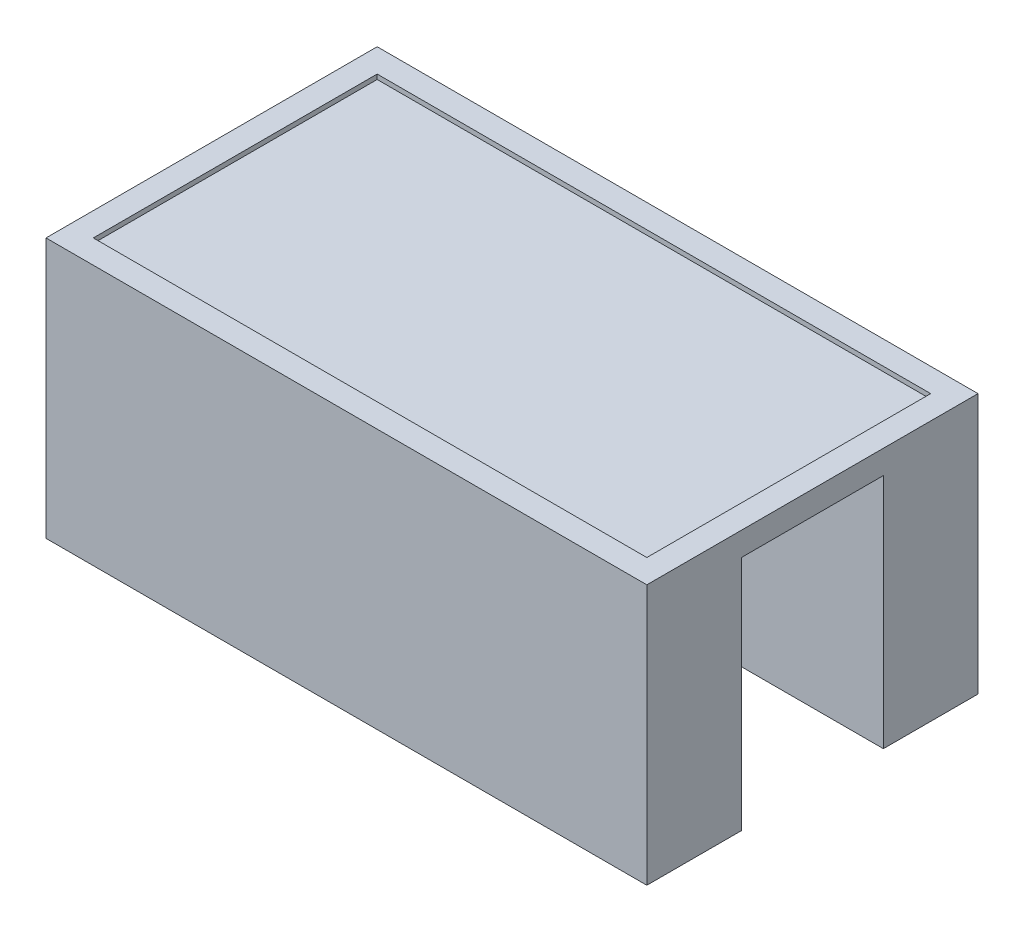
SolidWorks part; units mm, degrees
ref_plane "Front Plane" through (0, 0, 0) normal (0, 0, 1) x (1, 0, 0)
ref_plane "Top Plane" through (0, 0, 0) normal (0, 1, 0) x (1, 0, 0)
ref_plane "Right Plane" through (0, 0, 0) normal (1, 0, 0) x (0, 0, -1)
sketch "Sketch2" plane through (0, 0, 0) normal (0, 1, 0) x (1, 0, 0)
  line L1 (-63.5, 35) -> (63.5, 35)
  line L2 (-63.5, 35) -> (-63.5, -35)
  line L3 (-63.5, -35) -> (63.5, -35)
  line L4 (63.5, 35) -> (63.5, -35)
  line L5 (-63.5, 35) -> (63.5, -35) construction
  line L6 (-63.5, -35) -> (63.5, 35) construction
  point P0 (0, 0)
  dimension "D1" = 70
  dimension "D2" = 127
extrude "Boss-Extrude1" add sketch "Sketch2" along normal blind 55
sketch "Sketch4" plane through (0, 0, 0) normal (0, 1, 0) x (1, 0, 0)
  line L0 (63.5, -35) -> (63.5, 35) construction
  line L1 (-63.5, 15) -> (63.5, 15)
  line L2 (-63.5, 15) -> (-63.5, -15)
  line L3 (-63.5, -15) -> (63.5, -15)
  line L4 (63.5, 15) -> (63.5, -15)
  line L5 (-63.5, 15) -> (63.5, -15) construction
  line L6 (-63.5, -15) -> (63.5, 15) construction
  point P0 (0, 0)
  dimension "D1" = 30
extrude "Cut-Extrude1" cut sketch "Sketch4" along normal blind 50
sketch "Sketch5" plane through (0, 50, 0) normal (0, -1, 0) x (1, 0, 0)
  line L1 (-7.5, 11.5) -> (7.5, 11.5)
  line L2 (-7.5, 11.5) -> (-7.5, -11.5)
  line L3 (-7.5, -11.5) -> (7.5, -11.5)
  line L4 (7.5, 11.5) -> (7.5, -11.5)
  line L5 (-7.5, 11.5) -> (7.5, -11.5) construction
  line L6 (-7.5, -11.5) -> (7.5, 11.5) construction
  point P0 (0, 0)
  dimension "D1" = 23
  dimension "D2" = 15
extrude "Boss-Extrude2" add sketch "Sketch5" along normal blind 23
sketch "Sketch6" plane through (0, 27, 0) normal (0, -1, 0) x (1, 0, 0)
  line L0 (-7.5, -11.5) -> (7.5, -11.5) construction
  line L1 (6.5, 11.5) -> (3.5, 11.5)
  line L2 (6.5, 11.5) -> (6.5, -11.5)
  line L3 (6.5, -11.5) -> (3.5, -11.5)
  line L4 (3.5, 11.5) -> (3.5, -11.5)
  line L5 (6.5, 11.5) -> (3.5, -11.5) construction
  line L6 (6.5, -11.5) -> (3.5, 11.5) construction
  line L7 (7.5, -11.5) -> (7.5, 11.5) construction
  point P0 (5, 0)
  dimension "D1" = 3
  dimension "D2" = 1
extrude "Cut-Extrude2" cut sketch "Sketch6" against normal blind 23
ref_plane "Plane1" through (0, 27, 0) normal (0, 1, 0) x (1, 0, 0)
sketch "Sketch9" plane through (0, 27, 0) normal (0, 1, 0) x (1, 0, 0)
  line L1 (-7.5, 5) -> (7.5, 5)
  line L2 (-7.5, 5) -> (-7.5, -5)
  line L3 (-7.5, -5) -> (7.5, -5)
  line L4 (7.5, 5) -> (7.5, -5)
  line L5 (-7.5, 5) -> (7.5, -5) construction
  line L6 (-7.5, -5) -> (7.5, 5) construction
  point P0 (0, 0)
  dimension "D1" = 10
  dimension "D2" = 15
extrude "Cut-Extrude3" cut sketch "Sketch9" along normal blind 11.5
sketch "Sketch10" plane through (0, 55, 0) normal (0, 1, 0) x (1, 0, 0)
  line L1 (-58.5, 30) -> (58.5, 30)
  line L2 (-58.5, 30) -> (-58.5, -30)
  line L3 (-58.5, -30) -> (58.5, -30)
  line L4 (58.5, 30) -> (58.5, -30)
  line L5 (-58.5, 30) -> (58.5, -30) construction
  line L6 (-58.5, -30) -> (58.5, 30) construction
  point P0 (0, 0)
  dimension "D1" = 60
  dimension "D2" = 117
extrude "Cut-Extrude4" cut sketch "Sketch10" against normal blind 1
sketch "Sketch12" plane through (-7.5, 0, 0) normal (-1, 0, 0) x (0, 0, 1)
  line L0 (-14.0567, 50) -> (15, 50) construction
  line L1 (-15, 50) -> (15, 50) construction
  line L2 (15, 50) -> (15, 0) construction
  line L4 (0, 0) -> (0, 38.5) construction
  circle A0 centre (0, 38.5) radius 5
  dimension "D1" = 38.5
extrude "Cut-Extrude5" cut sketch "Sketch12" against normal blind 300
